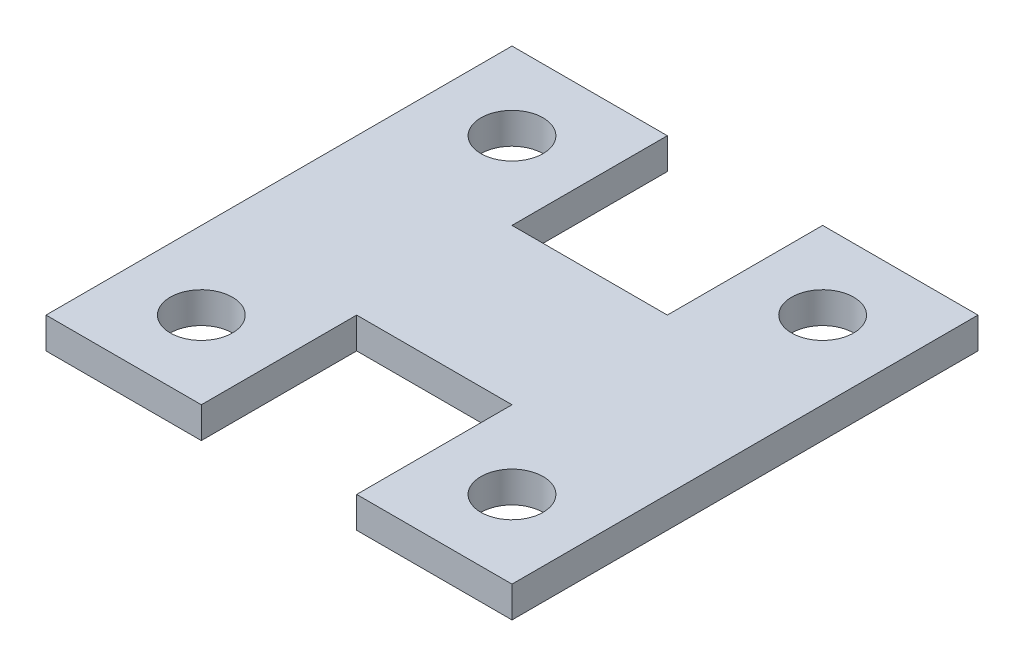
SolidWorks part; units mm, degrees
ref_plane "Front Plane" through (0, 0, 0) normal (0, 0, 1) x (1, 0, 0)
ref_plane "Top Plane" through (0, 0, 0) normal (0, 1, 0) x (1, 0, 0)
ref_plane "Right Plane" through (0, 0, 0) normal (1, 0, 0) x (0, 0, -1)
other "Center of Mass"
sketch "Sketch1" plane through (0, 0, 0) normal (0, 1, 0) x (1, 0, 0)
  line L0 (25, 75) -> (75, 75)
  line L1 (-75, 75) -> (-25, 75)
  line L2 (-75, 75) -> (-75, -75)
  line L3 (-75, -75) -> (-25, -75)
  line L4 (75, 75) -> (75, -75)
  line L5 (-75, 75) -> (75, -75) construction
  line L6 (-75, -75) -> (75, 75) construction
  line L8 (-25, 75) -> (-25, 25)
  line L9 (-25, 25) -> (25, 25)
  line L10 (25, 75) -> (25, 25)
  line L12 (-25, -75) -> (-25, -25)
  line L13 (-25, -25) -> (25, -25)
  line L14 (25, -75) -> (25, -25)
  line L15 (25, -75) -> (75, -75)
  line L17 (0, -82.5) -> (0, 82.5) construction
  line L18 (-82.5, 0) -> (82.5, 0) construction
  circle A0 centre (-50, 50) radius 10
  circle A1 centre (50, 50) radius 10
  circle A2 centre (50, -50) radius 10
  circle A3 centre (-50, -50) radius 10
  point P0 (0, 0)
  dimension "D9" = 25
  dimension "D11" = 20
  dimension "D1" = 150
  dimension "D2" = 150
  dimension "D3" = 50
  dimension "D4" = 50
  dimension "D5" = 50
  dimension "D6" = 50
  dimension "D7" = 50
  dimension "D8" = 50
  dimension "D10" = 25
extrude "Boss-Extrude1" add sketch "Sketch1" along normal blind 10
